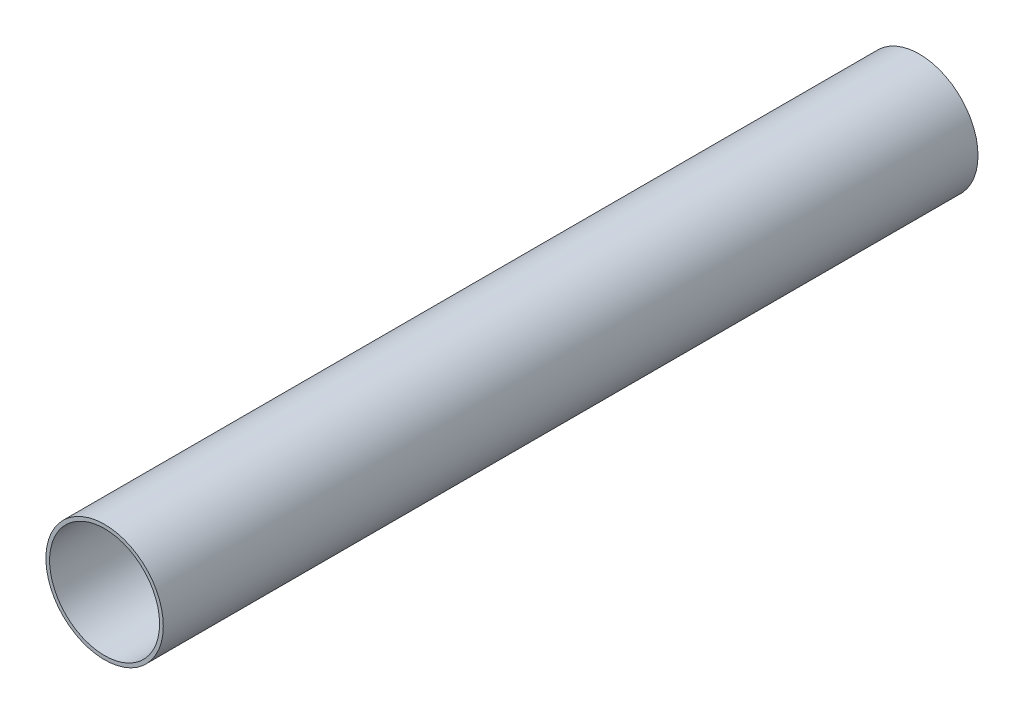
SolidWorks part; units mm, degrees
ref_plane "Plan de face" through (0, 0, 0) normal (0, 0, 1) x (1, 0, 0)
ref_plane "Plan de dessus" through (0, 0, 0) normal (0, 1, 0) x (1, 0, 0)
ref_plane "Plan de droite" through (0, 0, 0) normal (1, 0, 0) x (0, 0, -1)
sketch "Esquisse1" plane through (0, 0, 0) normal (0, 0, 1) x (1, 0, 0)
  circle A0 centre (0, 0) radius 15.85
  dimension "D1" = 31.7
extrude "Boss.-Extru.1" add sketch "Esquisse1" along normal blind 220
shell "Coque1" thickness 1
